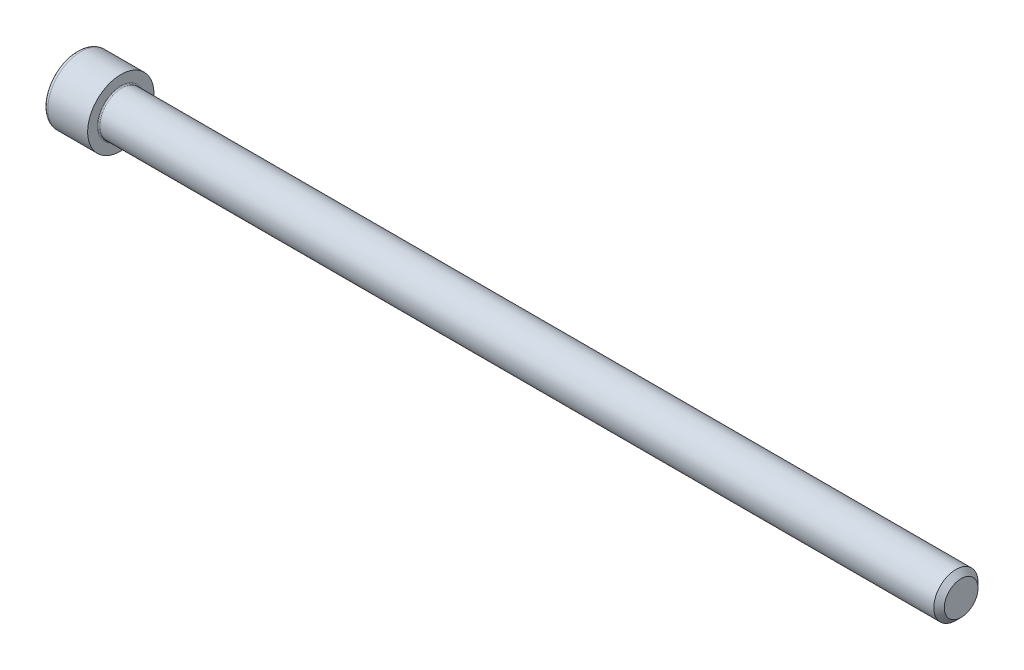
SolidWorks part; units mm, degrees
ref_plane "Front Plane" through (0, 0, 0) normal (0, 0, 1) x (1, 0, 0)
ref_plane "Top Plane" through (0, 0, 0) normal (0, 1, 0) x (1, 0, 0)
ref_plane "Right Plane" through (0, 0, 0) normal (1, 0, 0) x (0, 0, -1)
ref_plane "Plane1"
sketch "Sketch1" plane through (0, 0, 0) normal (0, 0, 1) x (1, 0, 0)
  line L0 (-1.7103, 0) -> (120.65, 0)
  line L1 (120.65, 0) -> (120.65, 3.175)
  line L2 (120.65, 3.175) -> (88.9, 3.175)
  line L3 (88.9, 3.175) -> (85.7249, 3.175)
  line L4 (85.7249, 3.175) -> (0, 3.175)
  line L5 (0, 3.175) -> (0, 4.7625)
  line L6 (0, 4.7625) -> (-6.35, 4.7625)
  line L7 (-6.35, 4.7625) -> (-6.35, 2.757)
  line L8 (-6.35, 2.757) -> (-3.302, 2.757)
  line L9 (-3.302, 2.757) -> (-1.7103, 0)
  line L10 (-1.7103, 0) -> (120.65, 0) construction
  dimension "D1" = 270
  dimension "D2" = 3.1751
  dimension "D3" = 6.35
  dimension "D4" = 3.048
  dimension "D5" = 120
  dimension "D6" = 3.175
  dimension "D7" = 3.175
  dimension "D8" = 2.757
  dimension "D9" = 4.7625
  dimension "D10" = 90
revolve "Body" add sketch "Sketch1" angle 360 about L10
cosmetic thread "Cosmetic Thread1" parameters "D1"=31.75, "D2"=4.8387
ref_plane "Plane2"
sketch "Sketch2" plane through (-6.35, 0, 0) normal (-1, 0, 0) x (0, 0, 1)
  line L0 (2.757, 0) -> (1.3785, -2.3876)
  line L1 (1.3785, -2.3876) -> (-1.3785, -2.3876)
  line L2 (-1.3785, -2.3876) -> (-2.757, 0)
  line L3 (-2.757, 0) -> (-1.3785, 2.3876)
  line L4 (-1.3785, 2.3876) -> (1.3785, 2.3876)
  line L5 (1.3785, 2.3876) -> (2.757, 0)
  circle A0 centre (0, 0) radius 2.757
extrude "Slot" add sketch "Sketch2" against normal up to next contours L0 A0 | L1 A0 | L2 A0 | L3 A0 | L4 A0 | L5 A0
fillet "Thread" radius 0.635 1 edges at (-6.35, -4.7625, 0)
chamfer "Chamfer1" distance 0.7556 distance2 0.7556 1 edges at (120.65, -3.175, 0)
fillet "Fillet2" radius 0.1778 1 edges at (0, -3.175, 0)
